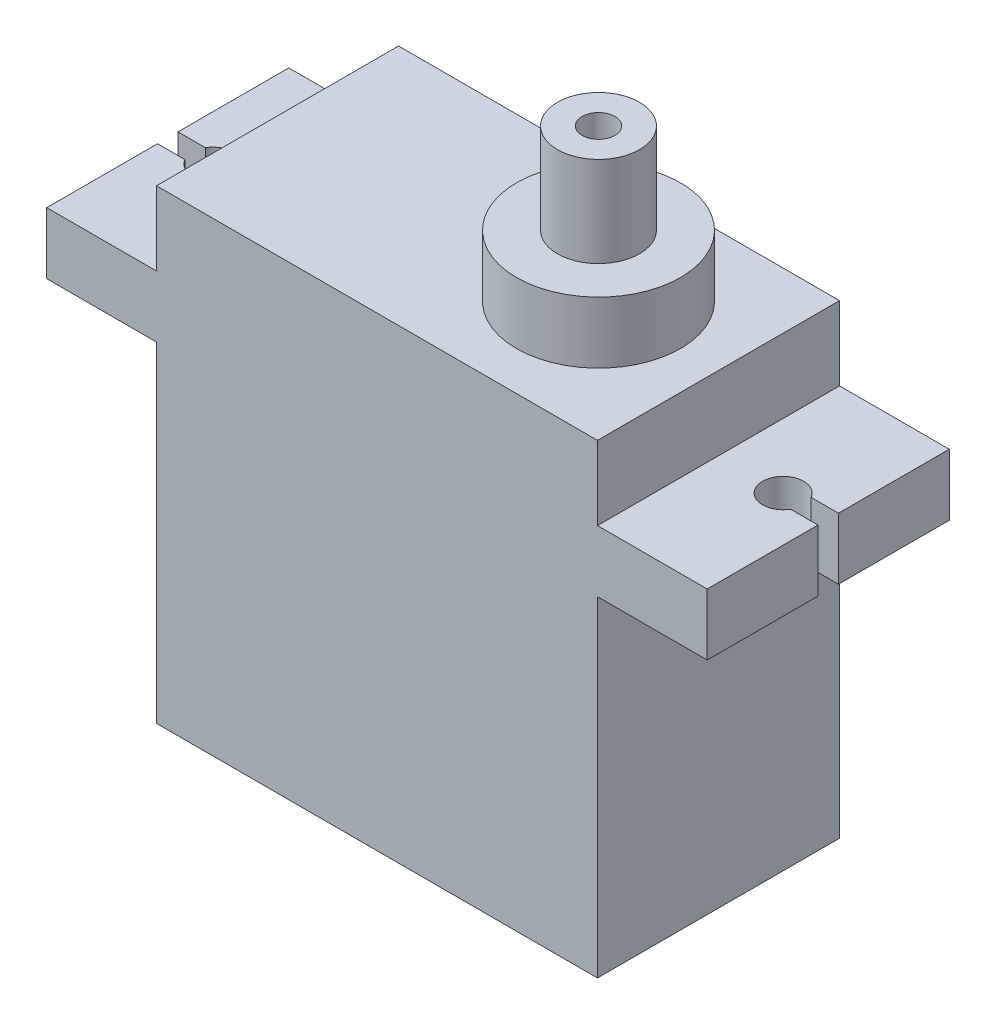
SolidWorks part; units mm, degrees
ref_plane "前视基准面" through (0, 0, 0) normal (0, 0, 1) x (1, 0, 0)
ref_plane "上视基准面" through (0, 0, 0) normal (0, 1, 0) x (1, 0, 0)
ref_plane "右视基准面" through (0, 0, 0) normal (1, 0, 0) x (0, 0, -1)
other "Configuration Table"
sketch "草图1" plane through (0, 0, 0) normal (0, 1, 0) x (1, 0, 0)
  line L1 (0, 0) -> (21.5, 0)
  line L2 (0, 0) -> (0, -11.8)
  line L3 (0, -11.8) -> (21.5, -11.8)
  line L4 (21.5, 0) -> (21.5, -11.8)
  dimension "D1" = 21.5
  dimension "D2" = 11.8
extrude "凸台-拉伸1" add sketch "草图1" along normal blind 22.7
ref_plane "基准面1" through (0, 16.1, 0) normal (0, 1, 0) x (1, 0, 0)
sketch "草图2" plane through (0, 16.1, 0) normal (0, 1, 0) x (1, 0, 0)
  line L0 (0, -11.8) -> (-5.35, -11.8)
  line L1 (-5.35, -11.8) -> (-5.35, 0)
  line L2 (-5.35, 0) -> (0, 0)
  line L3 (0, 0) -> (0, -11.8)
  line L4 (21.5, 0) -> (26.85, 0)
  line L5 (26.85, 0) -> (26.85, -11.8)
  line L6 (26.85, -11.8) -> (21.5, -11.8)
  line L7 (21.5, -11.8) -> (21.5, 0)
  line L8 (-5.35, -5.4) -> (-4.016, -5.4)
  line L9 (10.75, 0) -> (10.75, -7.054) construction
  line L10 (-5.35, -5.9) -> (-3.3138, -5.9) construction
  line L11 (0, -11.8) -> (21.5, -11.8) construction
  line L12 (-5.35, -6.4) -> (-4.016, -6.4)
  line L13 (26.85, -5.9) -> (24.8138, -5.9) construction
  line L14 (26.85, -6.4) -> (25.516, -6.4)
  line L15 (26.85, -5.4) -> (25.516, -5.4)
  circle A0 centre (-3.15, -5.9) radius 1
  circle A1 centre (24.65, -5.9) radius 1
  point P33 (10.75, -11.8)
  dimension "D3" = 2
  dimension "D1" = 32.2
  dimension "D2" = 1
  dimension "D4" = 27.8
extrude "凸台-拉伸2" add sketch "草图2" along normal blind 3
sketch "草图3" plane through (0, 22.7, 0) normal (0, 1, 0) x (1, 0, 0)
  line L0 (21.5, -11.8) -> (21.5, 0) construction
  line L1 (21.5, -5.9) -> (15.65, -5.9) construction
  line L2 (21.5, -11.8) -> (21.5, 0) construction
  circle A0 centre (15.65, -5.9) radius 0.8
  circle A1 centre (15.65, -5.9) radius 2
  dimension "D1" = 1.6
  dimension "D3" = 4
  dimension "D2" = 5.85
extrude "凸台-拉伸3" add sketch "草图3" along normal blind 7.4
sketch "草图6" plane through (0, 22.7, 0) normal (0, 1, 0) x (1, 0, 0)
  circle A0 centre (15.65, -5.9) radius 4
  dimension "D1" = 8
extrude "凸台-拉伸4" add sketch "草图6" along normal blind 3
